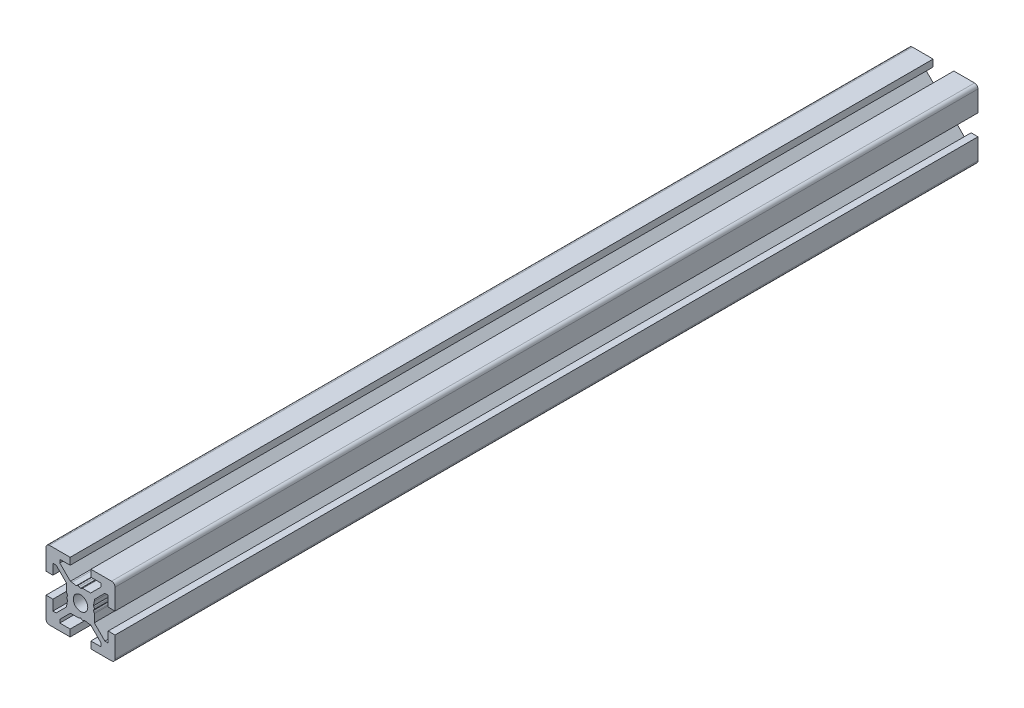
SolidWorks part; units mm, degrees
ref_plane "Front Plane" through (0, 0, 0) normal (0, 0, 1) x (1, 0, 0)
ref_plane "Top Plane" through (0, 0, 0) normal (0, 1, 0) x (1, 0, 0)
ref_plane "Right Plane" through (0, 0, 0) normal (1, 0, 0) x (0, 0, -1)
ref_plane "Plane1" through (0, 0, -2000) normal (0, 0, -1) x (-1, 0, 0)
sketch "Sketch1" plane through (0, 0, -2000) normal (0, 0, -1) x (-1, 0, 0)
  line L0 (10, -3) -> (8, -3)
  line L1 (8, -3) -> (8, -6)
  line L2 (8, -6) -> (7.0607, -6)
  line L3 (7.0607, -6) -> (4, -2.9393)
  line L4 (4, -2.9393) -> (4, -2.5)
  line L5 (4, -2.5) -> (3.751, -1.2189)
  line L6 (3.751, -1.2189) -> (3.933, -0.9036)
  line L7 (3.933, -0.4036) -> (3.7, 0)
  line L8 (3.7, 0) -> (3.933, 0.4036)
  line L9 (4, 0.6536) -> (4, 2.9393)
  line L10 (4, 2.9393) -> (7.0607, 6)
  line L11 (7.0607, 6) -> (8, 6)
  line L12 (8, 6) -> (8, 3)
  line L13 (8, 3) -> (10, 3)
  line L14 (10, 3) -> (10, 9)
  line L15 (9, 10) -> (3, 10)
  line L16 (3, 10) -> (3, 8)
  line L17 (3, 8) -> (6, 8)
  line L18 (6, 8) -> (6, 7.0607)
  line L19 (6, 7.0607) -> (2.9393, 4)
  line L20 (2.9393, 4) -> (2.5, 4)
  line L21 (2.5, 4) -> (1.2189, 3.751)
  line L22 (1.2189, 3.751) -> (0.9036, 3.933)
  line L23 (0.4036, 3.933) -> (0, 3.7)
  line L24 (0, 3.7) -> (-0.4036, 3.933)
  line L25 (-0.6536, 4) -> (-2.9393, 4)
  line L26 (-2.9393, 4) -> (-6, 7.0607)
  line L27 (-6, 7.0607) -> (-6, 8)
  line L28 (-6, 8) -> (-3, 8)
  line L29 (-3, 8) -> (-3, 10)
  line L30 (-3, 10) -> (-9, 10)
  line L31 (-10, 9) -> (-10, 3)
  line L32 (-10, 3) -> (-8, 3)
  line L33 (-8, 3) -> (-8, 6)
  line L34 (-8, 6) -> (-7.0607, 6)
  line L35 (-7.0607, 6) -> (-4, 2.9393)
  line L36 (-4, 2.9393) -> (-4, 2.5)
  line L37 (-4, 2.5) -> (-3.751, 1.2189)
  line L38 (-3.751, 1.2189) -> (-3.933, 0.9036)
  line L39 (-3.933, 0.4036) -> (-3.7, 0)
  line L40 (-3.7, 0) -> (-3.933, -0.4036)
  line L41 (-4, -0.6536) -> (-4, -2.9393)
  line L42 (-4, -2.9393) -> (-7.0607, -6)
  line L43 (-7.0607, -6) -> (-8, -6)
  line L44 (-8, -6) -> (-8, -3)
  line L45 (-8, -3) -> (-10, -3)
  line L46 (-10, -3) -> (-10, -9)
  line L47 (-9, -10) -> (-3, -10)
  line L48 (-3, -10) -> (-3, -8)
  line L49 (-3, -8) -> (-6, -8)
  line L50 (-6, -8) -> (-6, -7.0607)
  line L51 (-6, -7.0607) -> (-2.9393, -4)
  line L52 (-2.9393, -4) -> (-2.5, -4)
  line L53 (-2.5, -4) -> (-1.2189, -3.751)
  line L54 (-1.2189, -3.751) -> (-0.9036, -3.933)
  line L55 (-0.4036, -3.933) -> (0, -3.7)
  line L56 (0, -3.7) -> (0.4036, -3.933)
  line L57 (0.6536, -4) -> (2.9393, -4)
  line L58 (2.9393, -4) -> (6, -7.0607)
  line L59 (6, -7.0607) -> (6, -8)
  line L60 (6, -8) -> (3, -8)
  line L61 (3, -8) -> (3, -10)
  line L62 (3, -10) -> (9, -10)
  line L63 (10, -9) -> (10, -3)
  circle A0 centre (0, 0) radius 2.1
  arc A1 (3.933, -0.9036) -> (3.933, -0.4036) centre (3.5, -0.6536) ccw
  arc A2 (3.933, 0.4036) -> (4, 0.6536) centre (3.5, 0.6536) ccw
  arc A3 (10, 9) -> (9, 10) centre (9, 9) ccw
  arc A4 (0.9036, 3.933) -> (0.4036, 3.933) centre (0.6536, 3.5) ccw
  arc A5 (-0.4036, 3.933) -> (-0.6536, 4) centre (-0.6536, 3.5) ccw
  arc A6 (-9, 10) -> (-10, 9) centre (-9, 9) ccw
  arc A7 (-3.933, 0.9036) -> (-3.933, 0.4036) centre (-3.5, 0.6536) ccw
  arc A8 (-3.933, -0.4036) -> (-4, -0.6536) centre (-3.5, -0.6536) ccw
  arc A9 (-10, -9) -> (-9, -10) centre (-9, -9) ccw
  arc A10 (-0.9036, -3.933) -> (-0.4036, -3.933) centre (-0.6536, -3.5) ccw
  arc A11 (0.4036, -3.933) -> (0.6536, -4) centre (0.6536, -3.5) ccw
  arc A12 (9, -10) -> (10, -9) centre (9, -9) ccw
extrude "Boss-Extrude1" add sketch "Sketch1" against normal blind 250
